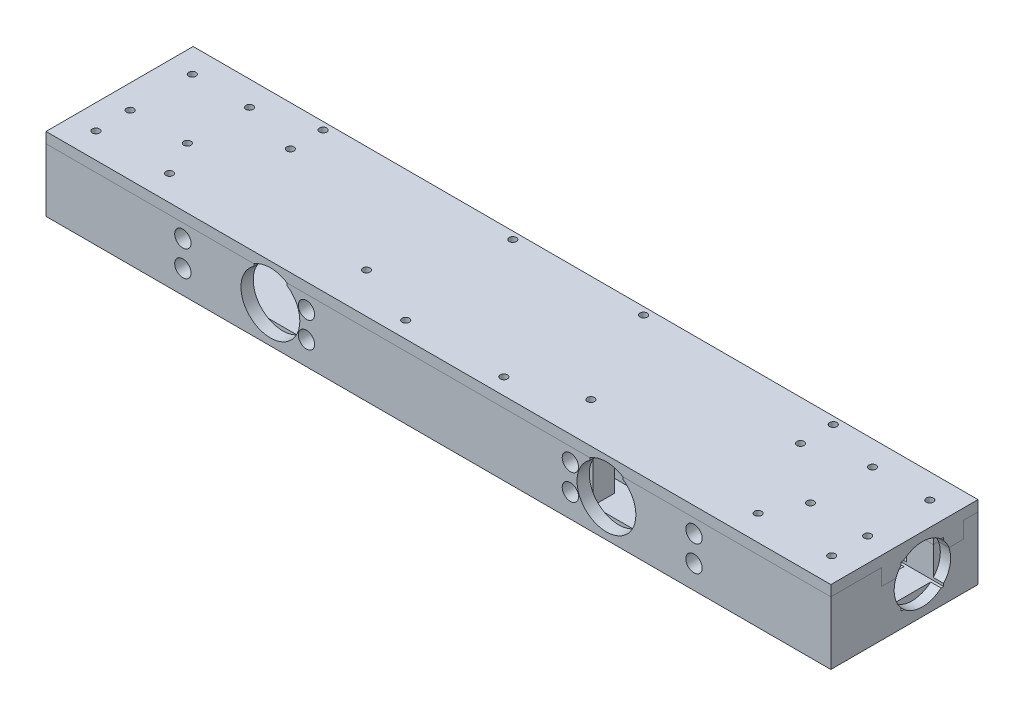
SolidWorks part; units mm, degrees
other "Bee-zerker Body Wedge"
other "Cam Top Plate"
other "Cam Body"
material "PLA/ABS"
ref_plane "Front Plane" through (0, 0, 0) normal (0, 0, 1) x (1, 0, 0)
ref_plane "Top Plane" through (0, 0, 0) normal (0, 1, 0) x (1, 0, 0)
ref_plane "Right Plane" through (0, 0, 0) normal (1, 0, 0) x (0, 0, -1)
sketch "Sketch1" plane through (0, 0, 0) normal (0, 1, 0) x (1, 0, 0)
  line L0 (-110.49, 0) -> (0, 0) construction
  line L1 (-152.4, -35.56) -> (152.4, -35.56)
  line L2 (-152.4, -35.56) -> (-152.4, 21.59)
  line L3 (-152.4, 21.59) -> (152.4, 21.59)
  line L4 (152.4, -35.56) -> (152.4, 21.59)
  line L5 (-152.4, -35.56) -> (152.4, 21.59) construction
  line L6 (-152.4, 21.59) -> (152.4, -35.56) construction
  line L11 (0, 0) -> (0, -6.985) construction
  line L12 (-65.25, 9.8025) -> (-65.25, -35.56) construction
  line L13 (-110.49, 0) -> (-171.45, 0) construction
  line L14 (-110.49, -10.9728) -> (-152.4, -10.9728)
  line L15 (-110.49, -10.9728) -> (-110.49, 10.9728)
  line L16 (-110.49, 10.9728) -> (-152.4, 10.9728)
  line L17 (-152.4, -10.9728) -> (-152.4, 10.9728)
  line L18 (-110.49, -10.9728) -> (-152.4, 10.9728) construction
  line L19 (-110.49, 10.9728) -> (-152.4, -10.9728) construction
  line L20 (-45.725, -0.1905) -> (7.9198, -0.1905)
  line L21 (-45.725, -0.1905) -> (-45.725, 16.8275)
  line L22 (-45.725, 16.8275) -> (7.9198, 16.8275)
  line L23 (7.9198, -0.1905) -> (7.9198, 16.8275)
  line L24 (-45.725, -0.1905) -> (7.9198, 16.8275) construction
  line L25 (-45.725, 16.8275) -> (7.9198, -0.1905) construction
  line L26 (-95.25, 9.8025) -> (-55.25, 9.8025)
  line L27 (-95.25, 9.8025) -> (-95.25, -30.7975)
  line L28 (-95.25, -30.7975) -> (-55.25, -30.7975)
  line L29 (-55.25, 9.8025) -> (-55.25, -30.7975)
  line L30 (-95.25, 9.8025) -> (-55.25, -30.7975) construction
  line L31 (-95.25, -30.7975) -> (-55.25, 9.8025) construction
  point P0 (0, -6.985)
  point P12 (-75.25, -10.4975)
  point P13 (-131.445, 0)
  point P19 (-18.9026, 8.3185)
  dimension "D1" = 304.8
  dimension "D2" = 57.15
  dimension "D3" = 21.59
  dimension "D4" = 40
  dimension "D5" = 17.018
  dimension "D6" = 41.91
  dimension "D7" = 21.9456
  dimension "D8" = 19.05
  dimension "D9" = 53.6448
  dimension "D10" = 40.6
  dimension "D11" = 57.15
  dimension "D12" = 4.7625
  dimension "D13" = 4.7625
  dimension "D14" = 9.525
  dimension "D15" = 10
sketch "Sketch2" plane through (0, 0, 0) normal (1, 0, 0) x (0, 0, -1)
  line L0 (-35.56, 11.1125) -> (-35.56, 39.6875)
  line L1 (-35.56, 39.6875) -> (21.59, 39.6875)
  line L2 (21.59, 39.6875) -> (21.59, 11.1125)
  line L3 (21.59, 11.1125) -> (-35.56, 11.1125)
  line L4 (-53.2447, 0) -> (-13.764, 0) construction
  line L5 (0, 25.4) -> (21.59, 25.4) construction
  line L6 (-35.56, 25.4) -> (0, 25.4) construction
  line L7 (-32.5269, 35.56) -> (49967.4731, 35.56) construction
  line L8 (-34.7846, 15.24) -> (49965.2154, 15.24) construction
  line L9 (21.59, 35.56) -> (0, 25.4) construction
  line L10 (0, 25.4) -> (21.59, 15.24) construction
  line L12 (-120.0634, 50.8) -> (-69.9767, 50.8) construction
  circle A0 centre (0, 25.4) radius 25.4
  circle A2 centre (0, 25.4) radius 10.9728
  point P9 (10.9728, 25.4)
  dimension "D1" = 50.8
  dimension "D2" = 28.575
  dimension "D3" = 20.32
sketch "Sketch3" plane through (0, 0, 0) normal (1, 0, 0) x (0, 0, -1)
  line L0 (-35.56, 11.1125) -> (-35.56, 39.6875)
  line L1 (-35.56, 39.6875) -> (21.59, 39.6875)
  line L2 (21.59, 39.6875) -> (21.59, 11.1125)
  line L3 (21.59, 11.1125) -> (-35.56, 11.1125)
extrude "Boss-Extrude1" add sketch "Sketch3" along normal up to vertex (152.4 mm away) and the other way up to vertex (152.4 mm away) up to point (152.4, 0, -21.59) other way up to point (-152.4, 0, -21.59)
sketch "Sketch6" plane through (152.4, 0, 0) normal (1, 0, 0) x (0, 0, -1)
  line L1 (-8.255, 33.655) -> (8.255, 33.655)
  line L2 (-8.255, 33.655) -> (-8.255, 17.145)
  line L3 (-8.255, 17.145) -> (8.255, 17.145)
  line L4 (8.255, 33.655) -> (8.255, 17.145)
  line L5 (-8.255, 33.655) -> (8.255, 17.145) construction
  line L6 (-8.255, 17.145) -> (8.255, 33.655) construction
  point P0 (0, 25.4)
  dimension "D1" = 16.51
extrude "Cut-Extrude2" cut sketch "Sketch6" against normal blind 16.9164
sketch "Sketch7" plane through (152.4, 0, 0) normal (1, 0, 0) x (0, 0, -1)
  circle A0 centre (0, 25.4) radius 10.9728 construction
  circle A1 centre (0, 25.4) radius 10.9728
extrude "Cut-Extrude3" cut sketch "Sketch7" against normal blind 4.0132
sketch "Sketch8" plane through (135.4836, 0, 0) normal (1, 0, 0) x (0, 0, -1)
  circle A0 centre (0, 25.4) radius 10.9728 construction
  circle A1 centre (0, 25.4) radius 10.9728
extrude "Cut-Extrude4" cut sketch "Sketch8" along normal blind 2.54
sketch "Sketch9" plane through (135.4836, 0, 0) normal (1, 0, 0) x (0, 0, -1)
  line L0 (7.7495, 32.0331) -> (7.7495, 18.7669)
  line L1 (-7.7495, 18.7669) -> (-7.7495, 32.0331)
  line L2 (-7.7495, 25.4) -> (7.7495, 25.4) construction
  arc A0 (7.7495, 32.0331) -> (-7.7495, 32.0331) centre (0, 25.4) ccw
  arc A1 (-7.7495, 18.7669) -> (7.7495, 18.7669) centre (0, 25.4) ccw
  dimension "D1" = 20.4013
  dimension "D2" = 15.4991
extrude "Cut-Extrude5" cut sketch "Sketch9" against normal blind 25.4
mirror "Mirror1" of "Cut-Extrude2", "Cut-Extrude3", "Cut-Extrude4", "Cut-Extrude5"
extrude "Cut-Extrude6" cut sketch "Sketch10" against normal up to surface (110.0836 mm away)
sketch "Sketch10" plane through (110.0836, 0, 0) normal (1, 0, 0) x (0, 0, -1)
  line L1 (-9.525, 33.1495) -> (9.525, 33.1495)
  line L2 (-9.525, 33.1495) -> (-9.525, 17.6505)
  line L3 (-9.525, 17.6505) -> (9.525, 17.6505)
  line L4 (9.525, 33.1495) -> (9.525, 17.6505)
  line L5 (-9.525, 33.1495) -> (9.525, 17.6505) construction
  line L6 (-9.525, 17.6505) -> (9.525, 33.1495) construction
  point P0 (0, 25.4)
  dimension "D1" = 19.05
  dimension "D2" = 15.4991
sketch "Sketch11" plane through (0, 0, 0) normal (1, 0, 0) x (0, 0, -1)
  line L0 (-35.56, 39.6875) -> (-35.56, 11.1125) construction
  line L1 (21.59, 39.6875) -> (-35.56, 39.6875) construction
  line L2 (-35.56, 35.56) -> (-15.875, 35.56)
  line L3 (-15.875, 35.56) -> (-15.875, 29.21)
  line L4 (-15.875, 29.21) -> (0, 29.21)
  line L5 (15.875, 29.21) -> (15.875, 35.56)
  line L6 (15.875, 35.56) -> (21.59, 35.56)
  line L9 (0, 11.1125) -> (0, 39.6875) construction
  line L10 (-35.56, 11.1125) -> (21.59, 11.1125) construction
  line L12 (0, 29.21) -> (15.875, 29.21)
  line L13 (-35.56, 11.1125) -> (-35.56, 39.6875) construction
  line L14 (-200032.5269, 35.56) -> (249967.4731, 35.56) construction
  dimension "D1" = 10.4775
  dimension "D4" = 15.875
split "Split1" trim tools "Sketch11" bodies to split 113 resulting bodies 178 179
sketch "Sketch13" plane through (0, 11.1125, 0) normal (0, 1, 0) x (1, 0, 0)
  line L1 (-102.87, -15.875) -> (-102.87, 9.8025)
  line L3 (-110.0836, 15.875) -> (110.0836, 15.875)
  line L5 (-102.87, 9.8025) -> (-95.25, 9.8025)
  line L7 (110.0836, 15.875) -> (110.0836, -15.875)
  line L8 (-152.4, -15.875) -> (152.4, -15.875) construction
  line L10 (-152.4, -15.875) -> (152.4, -15.875) construction
  line L12 (-95.25, 9.8025) -> (-95.25, -30.7975)
  line L16 (-110.0836, -15.875) -> (-110.0836, 15.875)
  line L18 (-110.0836, 7.7495) -> (-110.0836, -7.7495) construction
  line L19 (-152.4, 15.875) -> (152.4, 15.875) construction
  line L21 (-55.25, -30.7975) -> (-55.25, 9.8025)
  line L23 (-55.25, 9.8025) -> (-47.63, 9.8025)
  line L24 (-110.0836, -15.875) -> (-102.87, -15.875)
  line L25 (0, -15.875) -> (0, 0) construction
  line L27 (-47.63, 9.8025) -> (-47.63, -15.875)
  line L28 (-95.25, -30.7975) -> (-55.25, -30.7975)
  line L29 (-47.63, -15.875) -> (47.63, -15.875)
  line L30 (47.63, -15.875) -> (47.63, 9.8025)
  line L31 (47.63, 9.8025) -> (55.25, 9.8025)
  line L32 (55.25, 9.8025) -> (55.25, -30.7975)
  line L33 (95.25, -30.7975) -> (95.25, 9.8025)
  line L35 (95.25, 9.8025) -> (102.87, 9.8025)
  line L36 (102.87, 9.8025) -> (102.87, -15.875)
  line L37 (55.25, -30.7975) -> (95.25, -30.7975)
  line L38 (102.87, -15.875) -> (110.0836, -15.875)
  line L39 (110.0836, -7.7495) -> (110.0836, 7.7495) construction
  line L40 (-152.4, -15.875) -> (152.4, -15.875) construction
  line L41 (-95.25, 9.8025) -> (-95.25, -30.7975) construction
  dimension "D1" = 7.62
extrude "Cut-Extrude7" cut sketch "Sketch13" along normal up to surface (20.32 mm away) from vertex at 4.1275 up to face at (0, 35.56, 25.7175) starting at point (0, 15.24, -21.59)
sketch "Sketch15" plane through (0, 0, 35.56) normal (0, 0, 1) x (1, 0, 0)
  line L0 (-95.25, 15.24) -> (-55.25, 15.24) construction
  line L1 (-95.25, 15.24) -> (-55.25, 15.24) construction
  line L2 (-71.7, 25.24) -> (-71.7, 35.56)
  line L3 (152.4, 35.56) -> (-152.4, 35.56) construction
  line L4 (-71.7, 35.56) -> (-58.8, 35.56)
  line L5 (-58.8, 35.56) -> (-58.8, 25.24)
  arc A0 (-71.7, 25.24) -> (-58.8, 25.24) centre (-65.25, 25.24) ccw
  arc A1 (-58.8, 25.24) -> (-71.7, 25.24) centre (-65.25, 25.24) ccw construction
  dimension "D1" = 12.9
  dimension "D2" = 10
extrude "Cut-Extrude8" cut sketch "Sketch15" against normal up to next (4.7625 mm away)
sketch "Sketch16" plane through (0, 35.56, 0) normal (0, 1, 0) x (1, 0, 0)
  line L0 (-95.25, 9.8025) -> (-95.25, -30.7975) construction
  line L1 (-95.25, -22.4775) -> (-102.87, -22.4775)
  line L2 (-95.25, -22.4775) -> (-95.25, -17.3975)
  line L3 (-95.25, -17.3975) -> (-102.87, -17.3975)
  line L4 (-102.87, -22.4775) -> (-102.87, -17.3975)
  line L5 (-95.25, -22.4775) -> (-102.87, -17.3975) construction
  line L6 (-95.25, -17.3975) -> (-102.87, -22.4775) construction
  line L7 (-55.25, 9.8025) -> (-55.25, -30.7975) construction
  line L8 (-55.25, -22.4775) -> (-47.63, -22.4775)
  line L9 (-55.25, -22.4775) -> (-55.25, -17.3975)
  line L10 (-55.25, -17.3975) -> (-47.63, -17.3975)
  line L11 (-47.63, -22.4775) -> (-47.63, -17.3975)
  line L12 (-55.25, -22.4775) -> (-47.63, -17.3975) construction
  line L13 (-55.25, -17.3975) -> (-47.63, -22.4775) construction
  line L14 (-95.25, 9.8025) -> (-55.25, 9.8025) construction
  point P4 (-99.06, -19.9375)
  point P11 (-51.44, -19.9375)
  dimension "D1" = 27.2
  dimension "D2" = 7.62
  dimension "D3" = 5.08
extrude "Cut-Extrude9" cut sketch "Sketch16" against normal up to surface (20.32 mm away) up to face at (0, 15.24, 4.5112)
sketch "Sketch17" plane through (0, 29.21, 0) normal (0, 1, 0) x (1, 0, 0)
  line L1 (-102.87, -15.875) -> (-95.25, -15.875)
  line L2 (-102.87, -15.875) -> (-102.87, 9.8025)
  line L3 (-102.87, 9.8025) -> (-95.25, 9.8025)
  line L4 (-95.25, -15.875) -> (-95.25, 9.8025)
  line L5 (-102.87, -15.875) -> (-95.25, 9.8025) construction
  line L6 (-102.87, 9.8025) -> (-95.25, -15.875) construction
  line L7 (-47.63, -15.875) -> (-55.25, -15.875)
  line L8 (-47.63, -15.875) -> (-47.63, 9.8025)
  line L9 (-47.63, 9.8025) -> (-55.25, 9.8025)
  line L10 (-55.25, -15.875) -> (-55.25, 9.8025)
  line L11 (-47.63, -15.875) -> (-55.25, 9.8025) construction
  line L12 (-47.63, 9.8025) -> (-55.25, -15.875) construction
  point P4 (-99.06, -3.0362)
  point P11 (-51.44, -3.0362)
extrude "Boss-Extrude2" add sketch "Sketch17" along normal up to surface (6.35 mm away) up to face at (12.2814, 35.56, 24.1114)
sketch "Sketch18" plane through (0, 15.24, 0) normal (0, 1, 0) x (1, 0, 0)
  line L0 (110.0836, 15.875) -> (-110.0836, 15.875) construction
  line L1 (-102.87, 9.8025) -> (-47.63, 9.8025)
  line L2 (-102.87, 9.8025) -> (-102.87, 15.875)
  line L3 (-102.87, 15.875) -> (-47.63, 15.875)
  line L4 (-47.63, 9.8025) -> (-47.63, 15.875)
  line L5 (-102.87, 9.8025) -> (-47.63, 15.875) construction
  line L6 (-102.87, 15.875) -> (-47.63, 9.8025) construction
  line L7 (-55.25, 9.8025) -> (-47.63, 9.8025) construction
  line L8 (-55.25, 9.8025) -> (-47.63, 9.8025) construction
  point P4 (-75.25, 12.8387)
extrude "Boss-Extrude3" add sketch "Sketch18" along normal blind 9.525
sketch "Sketch19" plane through (-55.25, 0, 0) normal (-1, 0, 0) x (0, 0, 1)
  line L0 (-9.8025, 21.59) -> (-1.8025, 21.59)
  line L1 (-9.8025, 24.765) -> (-9.8025, 15.24) construction
  line L2 (-1.8025, 21.59) -> (-1.8025, 29.21)
  line L3 (-1.8025, 29.21) -> (-9.8025, 29.21)
  line L5 (-9.8025, 29.21) -> (-9.8025, 21.59)
  line L6 (17.3975, 15.24) -> (-9.8025, 15.24) construction
  line L8 (17.3975, 25.4) -> (-1.8025, 25.4) construction
  line L9 (17.3975, 15.24) -> (17.3975, 35.56) construction
  dimension "D1" = 6.35
  dimension "D3" = 8
extrude "Cut-Extrude10" cut sketch "Sketch19" against normal up to surface (7.62 mm away) up to face at (-47.63, 32.385, 3.0362)
sketch "Sketch20" plane through (0, 0, 35.56) normal (0, 0, 1) x (1, 0, 0)
  line L0 (-55.25, 15.24) -> (-47.63, 15.24) construction
  line L1 (-47.63, 15.24) -> (-47.63, 35.56) construction
  line L2 (-47.63, 35.56) -> (-55.25, 35.56) construction
  line L3 (-55.25, 35.56) -> (-55.25, 15.24) construction
  line L4 (-102.87, 15.24) -> (-95.25, 15.24) construction
  line L5 (-95.25, 15.24) -> (-95.25, 35.56) construction
  line L6 (-95.25, 35.56) -> (-102.87, 35.56) construction
  line L7 (-102.87, 35.56) -> (-102.87, 15.24) construction
  line L8 (-55.25, 15.24) -> (-47.63, 15.24) construction
  line L9 (-47.63, 15.24) -> (-47.63, 35.56) construction
  line L10 (-47.63, 35.56) -> (-55.25, 35.56) construction
  line L11 (-55.25, 35.56) -> (-55.25, 15.24) construction
  line L12 (-102.87, 15.24) -> (-95.25, 15.24) construction
  line L13 (-95.25, 15.24) -> (-95.25, 35.56) construction
  line L14 (-95.25, 35.56) -> (-102.87, 35.56) construction
  line L15 (-102.87, 35.56) -> (-102.87, 15.24) construction
  line L16 (-99.25, 20.24) -> (-99.25, 30.24) construction
  line L17 (-51.25, 20.24) -> (-51.25, 30.24) construction
  line L18 (-99.25, 25.24) -> (-95.25, 25.24) construction
  line L20 (-95.25, 25.24) -> (-65.25, 25.24) construction
  line L21 (-65.25, 25.24) -> (-55.25, 25.24) construction
  line L22 (-55.25, 25.24) -> (-51.25, 25.24) construction
  circle A0 centre (-99.25, 20.24) radius 3.175
  circle A1 centre (-99.25, 30.24) radius 3.175
  circle A2 centre (-51.25, 20.24) radius 3.175
  circle A3 centre (-51.25, 30.24) radius 3.175
  circle A4 centre (-65.25, 25.24) radius 6.45 construction
  circle A5 centre (-65.25, 25.24) radius 6.45 construction
  dimension "D2" = 6.35
  dimension "D1" = 4
  dimension "D3" = 10
extrude "Cut-Extrude11" cut sketch "Sketch20" against normal up to surface (18.1625 mm away) up to face at (-99.06, 25.4, 17.3975)
sketch "Sketch21" plane through (0, 0, 17.3975) normal (0, 0, 1) x (1, 0, 0)
  circle A0 centre (-99.25, 30.24) radius 1.397
  circle A1 centre (-99.25, 20.24) radius 1.397
  circle A2 centre (-51.25, 20.24) radius 1.397
  circle A3 centre (-51.25, 30.24) radius 1.397
  dimension "D1" = 2.794
extrude "Cut-Extrude12" cut sketch "Sketch21" against normal blind 25.4
sketch "Sketch28" plane through (0, 0, 35.56) normal (0, 0, 1) x (1, 0, 0)
  circle A0 centre (-65.25, 25.24) radius 11.43
  dimension "D1" = 22.86
extrude "Cut-Extrude16" cut sketch "Sketch28" against normal blind 4.7625
mirror "Mirror2" about plane through (0, 0, 0) normal (1, 0, 0) of "Cut-Extrude16", "Cut-Extrude12", "Cut-Extrude11", "Cut-Extrude10", "Boss-Extrude3", "Boss-Extrude2", "Cut-Extrude9", "Cut-Extrude8"
sketch "Sketch23" plane through (0, 35.56, 0) normal (0, 1, 0) x (1, 0, 0)
  line L0 (-102.87, -15.875) -> (-102.87, 15.875) construction
  line L1 (-110.0836, -15.875) -> (-102.87, -15.875)
  line L2 (-110.0836, -15.875) -> (-110.0836, -9.525)
  line L3 (-110.0836, -9.525) -> (-102.87, -9.525)
  line L4 (-102.87, -15.875) -> (-102.87, -9.525)
  line L5 (-110.0836, -15.875) -> (-102.87, -9.525) construction
  line L6 (-110.0836, -9.525) -> (-102.87, -15.875) construction
  line L7 (102.87, -15.875) -> (102.87, 9.8025) construction
  line L8 (110.0836, -15.875) -> (102.87, -15.875)
  line L9 (110.0836, -15.875) -> (110.0836, -9.525)
  line L10 (110.0836, -9.525) -> (102.87, -9.525)
  line L11 (102.87, -15.875) -> (102.87, -9.525)
  line L12 (110.0836, -15.875) -> (102.87, -9.525) construction
  line L13 (110.0836, -9.525) -> (102.87, -15.875) construction
  point P4 (-106.4768, -12.7)
  point P12 (106.4768, -12.7)
  dimension "D1" = 9.525
extrude "Boss-Extrude5" add sketch "Sketch23" against normal up to surface (20.32 mm away) up to face at (-73.8214, 15.24, 18.7918)
sketch "Sketch24" plane through (0, 35.56, 0) normal (0, -1, 0) x (1, 0, 0)
  line L0 (-152.4, -15.875) -> (-110.0836, -15.875) construction
  line L1 (-102.87, -9.8025) -> (-47.63, -9.8025)
  line L2 (-102.87, -9.8025) -> (-102.87, -15.875)
  line L3 (-102.87, -15.875) -> (-47.63, -15.875)
  line L4 (-47.63, -9.8025) -> (-47.63, -15.875)
  line L5 (-102.87, -9.8025) -> (-47.63, -15.875) construction
  line L6 (-102.87, -15.875) -> (-47.63, -9.8025) construction
  line L8 (47.63, -9.8025) -> (102.87, -9.8025)
  line L9 (47.63, -9.8025) -> (47.63, -15.875)
  line L10 (47.63, -15.875) -> (102.87, -15.875)
  line L11 (102.87, -9.8025) -> (102.87, -15.875)
  line L12 (47.63, -9.8025) -> (102.87, -15.875) construction
  line L13 (47.63, -15.875) -> (102.87, -9.8025) construction
  point P4 (-75.25, -12.8387)
  point P14 (75.25, -12.8387)
extrude "Boss-Extrude6" add sketch "Sketch24" along normal blind 3.175
sketch "Sketch25" plane through (0, 29.21, 0) normal (0, -1, 0) x (1, 0, 0)
  line L1 (-102.87, -9.8025) -> (102.87, -9.8025)
  line L2 (-102.87, -9.8025) -> (-102.87, 15.875)
  line L3 (-102.87, 15.875) -> (102.87, 15.875)
  line L4 (102.87, -9.8025) -> (102.87, 15.875)
  line L5 (-102.87, -9.8025) -> (102.87, 15.875) construction
  line L6 (-102.87, 15.875) -> (102.87, -9.8025) construction
  point P4 (0, 3.0362)
extrude "Cut-Extrude13" cut sketch "Sketch25" against normal up to surface (6.35 mm away) up to face at (0, 35.56, 1.7463)
sketch "Sketch26" plane through (0, 39.6875, 0) normal (0, 1, 0) x (1, 0, 0)
  line L0 (-142.875, -35.56) -> (-142.875, -25.7175) construction
  line L1 (152.4, -35.56) -> (-152.4, -35.56) construction
  line L2 (-142.875, -25.7175) -> (-142.875, -15.875) construction
  line L3 (-142.875, -25.7175) -> (-114.3, -25.7175) construction
  line L4 (-142.875, -25.7175) -> (-152.4, -25.7175) construction
  line L5 (-152.4, 21.59) -> (-152.4, -35.56) construction
  line L6 (-152.4, -15.875) -> (-110.0836, -15.875) construction
  line L7 (-95.25, -22.4775) -> (-95.25, -30.7975) construction
  line L8 (-143.2052, 8.255) -> (-143.2052, 12.065) construction
  line L9 (-148.3868, 8.255) -> (-138.0236, 8.255) construction
  line L10 (-143.2052, 12.065) -> (-143.2052, 15.875) construction
  line L11 (-152.4, 15.875) -> (152.4, 15.875) construction
  line L12 (-143.2052, -8.255) -> (-143.2052, -12.065) construction
  line L13 (-138.0236, -8.255) -> (-148.3868, -8.255) construction
  line L14 (-143.2052, -12.065) -> (-143.2052, -15.875) construction
  line L15 (-152.4, -15.875) -> (-110.0836, -15.875) construction
  line L16 (-143.2052, -12.065) -> (-120.9802, -12.065) construction
  line L17 (-143.2052, 12.065) -> (-120.9802, 12.065) construction
  line L18 (-99.06, 9.8025) -> (-99.06, 5.9925) construction
  line L19 (-102.87, 9.8025) -> (-95.25, 9.8025) construction
  line L20 (-99.06, 5.9925) -> (-95.25, 5.9925) construction
  line L21 (-95.25, -17.3975) -> (-95.25, 9.8025) construction
  line L22 (-99.06, 5.9925) -> (-102.87, 5.9925) construction
  line L23 (-102.87, -9.525) -> (-102.87, 9.8025) construction
  line L24 (-99.06, 15.875) -> (-99.06, 18.7325) construction
  line L25 (-99.06, 18.7325) -> (-99.06, 21.59) construction
  line L26 (-152.4, 21.59) -> (152.4, 21.59) construction
  line L27 (-99.06, 18.7325) -> (-25.4, 18.7325) construction
  line L28 (-47.63, -19.9375) -> (-43.5675, -19.9375) construction
  line L29 (-47.63, -22.4775) -> (-47.63, -17.3975) construction
  line L30 (-43.5675, -19.9375) -> (-43.5675, -15.875) construction
  line L31 (-47.63, -15.875) -> (47.63, -15.875) construction
  line L32 (58.8, -35.56) -> (-58.8, -35.56) construction
  circle A0 centre (-142.875, -25.7175) radius 1.397
  circle A1 centre (-114.3, -25.7175) radius 1.397
  circle A3 centre (-99.06, 5.9925) radius 1.397
  circle A4 centre (-143.2052, 12.065) radius 1.397
  circle A5 centre (-120.9802, 12.065) radius 1.397
  circle A6 centre (-143.2052, -12.065) radius 1.397
  circle A7 centre (-120.9802, -12.065) radius 1.397
  circle A8 centre (-99.06, 18.7325) radius 1.397
  circle A10 centre (-25.4, 18.7325) radius 1.397
  circle A13 centre (-43.5675, -19.9375) radius 1.397
  circle A14 centre (-19.05, -29.21) radius 1.397
  dimension "D1" = 2.794
  dimension "D2" = 9.525
  dimension "D3" = 19.05
  dimension "D4" = 22.225
  dimension "D5" = 25.4
  dimension "D6" = 19.05
  dimension "D7" = 6.35
extrude "Cut-Extrude14" cut sketch "Sketch26" against normal blind 25.4
mirror "Mirror3" about plane through (0, 0, 0) normal (1, 0, 0) of "Cut-Extrude14"
sketch "Sketch27" plane through (0, 35.56, 0) normal (0, 1, 0) x (1, 0, 0)
  line L0 (-40.01, -15.875) -> (-34.1441, -26.035)
  line L1 (-47.63, -15.875) -> (47.63, -15.875) construction
  line L2 (-34.1441, -26.035) -> (34.1441, -26.035)
  line L3 (34.1441, -26.035) -> (40.01, -15.875)
  line L4 (40.01, -15.875) -> (-40.01, -15.875)
  line L5 (0, -15.875) -> (0, 0) construction
  circle A0 centre (-19.05, -29.21) radius 1.397 construction
  dimension "D1" = 3.175
  dimension "D2" = 60
  dimension "D3" = 7.62
extrude "Cut-Extrude15" cut sketch "Sketch27" against normal up to surface (20.32 mm away) up to face at (-73.8214, 15.24, 18.7918)
sketch "Sketch31" plane through (0, 0, 35.56) normal (0, 0, 1) x (1, 0, 0)
  line L0 (152.4, 35.56) -> (-152.4, 35.56) construction
  line L1 (-71.7, 35.56) -> (-58.8, 35.56)
  line L2 (-58.8, 34.6762) -> (-58.8, 35.56) construction
  line L3 (-47.63, 35.56) -> (-102.87, 35.56) construction
  line L4 (152.4, 35.56) -> (71.7, 35.56) construction
  line L5 (71.7, 35.56) -> (71.7, 34.6762) construction
  line L6 (58.8, 35.56) -> (71.7, 35.56)
  arc A0 (-71.7, 35.56) -> (-58.8, 35.56) centre (-65.25, 25.24) cw
  arc A2 (58.8, 35.56) -> (71.7, 35.56) centre (65.25, 25.24) cw
  arc A4 (58.8, 34.6762) -> (71.7, 34.6762) centre (65.25, 25.24) ccw construction
  arc A5 (-71.7, 34.6762) -> (-58.8, 34.6762) centre (-65.25, 25.24) ccw construction
  point P3 (0, 0)
extrude "Cut-Extrude17" cut sketch "Sketch31" against normal up to surface (4.7625 mm away) up to face at (-82.0221, 27.2042, 30.7975)
other "Save Bodies1"
